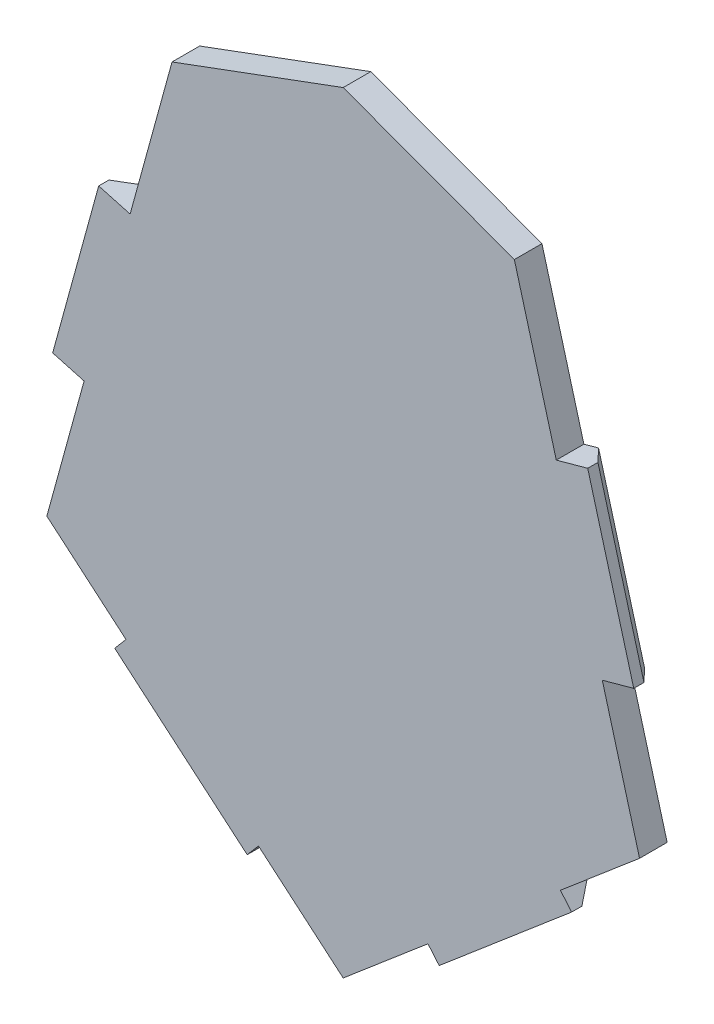
SolidWorks part; units mm, degrees
ref_plane "Front Plane" through (0, 0, 0) normal (0, 0, 1) x (1, 0, 0)
ref_plane "Top Plane" through (0, 0, 0) normal (0, 1, 0) x (1, 0, 0)
ref_plane "Right Plane" through (0, 0, 0) normal (1, 0, 0) x (0, 0, -1)
sketch "Sketch1" plane through (0, 0, 0) normal (0, 0, 1) x (1, 0, 0)
  line L6 (0, 56.7852) -> (0, -31.9448) construction
  line L7 (0, 56.7852) -> (-19.6925, 49.4909)
  line L8 (0, 56.7852) -> (19.6925, 49.4909)
  line L9 (-19.6925, 49.4909) -> (-34.0985, -2.9708)
  line L10 (-34.0985, -2.9708) -> (0, -31.9448)
  line L11 (0, -31.9448) -> (34.0985, -2.9708)
  line L12 (34.0985, -2.9708) -> (19.6925, 49.4909)
  line L13 (24.5171, 31.9213) -> (28.1333, 32.9143)
  line L14 (28.1333, 32.9143) -> (33.4292, 13.6283)
  line L15 (33.4292, 13.6283) -> (29.8131, 12.6353)
  line L16 (24.5171, 31.9213) -> (29.8131, 12.6353)
  line L17 (-24.5171, 31.9213) -> (-28.1333, 32.9143)
  line L18 (-28.1333, 32.9143) -> (-33.4292, 13.6283)
  line L19 (-33.4292, 13.6283) -> (-29.8131, 12.6353)
  line L20 (-24.5171, 31.9213) -> (-29.8131, 12.6353)
  line L21 (24.9921, -10.7087) -> (26.2871, -12.2328)
  line L22 (26.2871, -12.2328) -> (11.0462, -25.1832)
  line L23 (11.0462, -25.1832) -> (9.7511, -23.6591)
  line L24 (9.7511, -23.6591) -> (24.9921, -10.7087)
  line L25 (-24.9921, -10.7087) -> (-26.2871, -12.2328)
  line L26 (-26.2871, -12.2328) -> (-11.0462, -25.1832)
  line L27 (-11.0462, -25.1832) -> (-9.7511, -23.6591)
  line L28 (-9.7511, -23.6591) -> (-24.9921, -10.7087)
  dimension "D1" = 88.73
  dimension "D2" = 21
  dimension "D3" = 21
  dimension "D4" = 139.35
  dimension "D5" = 125.68
  dimension "D6" = 125.68
  dimension "D7" = 115
  dimension "D8" = 115
  dimension "D9" = 20
  dimension "D10" = 3.75
  dimension "D11" = 3.75
  dimension "D12" = 20
  dimension "D13" = 18.22
  dimension "D14" = 18.22
  dimension "D15" = 90
  dimension "D16" = 90
  dimension "D17" = 20
  dimension "D18" = 2
  dimension "D19" = 2
  dimension "D20" = 11.95
  dimension "D21" = 11.95
  dimension "D22" = 20
extrude "Boss-Extrude1" add sketch "Sketch1" along normal blind 3.175 contours L18 L19 L9 L17 | L6 L7 L9 L10 | L8 L6 L11 L12 | L15 L14 L13 L12 | L26 L27 L10 L25 | L22 L23 L24 L21
chamfer "Chamfer1" distance 2 angle 45 4 edges at (18.6667, -18.708, 0) (-18.6667, -18.708, 0) (-30.7812, 23.2713, 0) (30.7812, 23.2713, 0)
